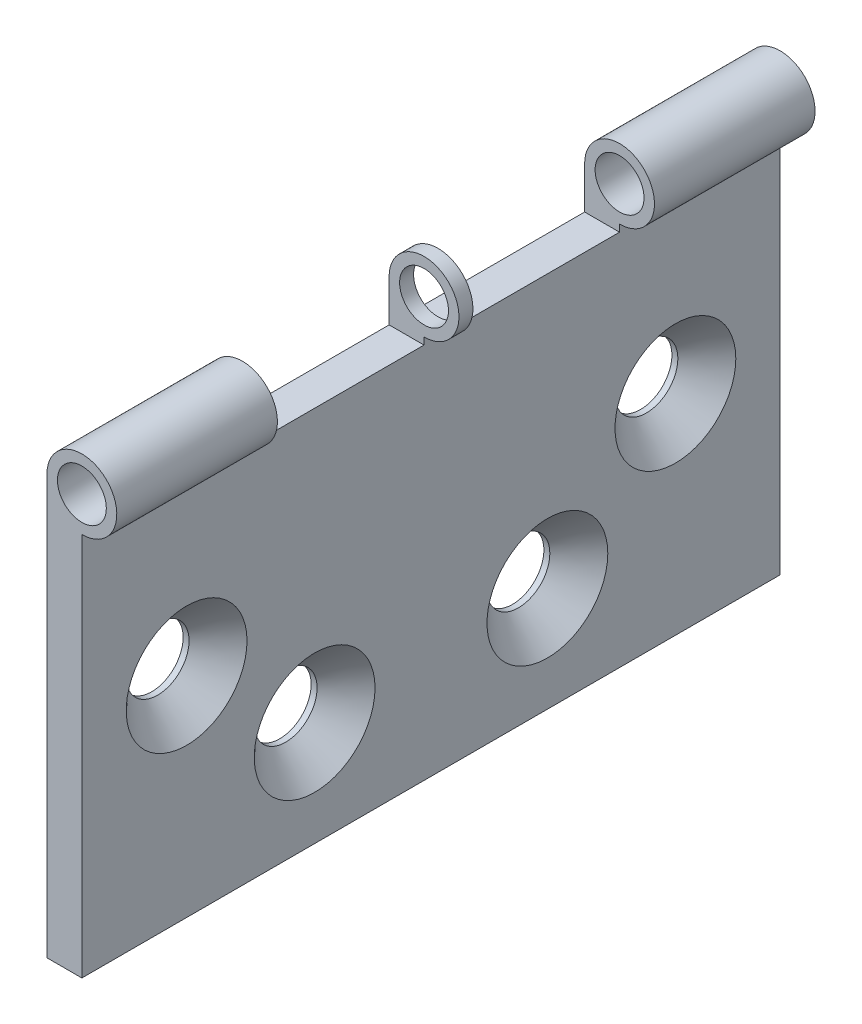
SolidWorks part; units mm, degrees
ref_plane "Front Plane" through (0, 0, 0) normal (0, 0, 1) x (1, 0, 0)
ref_plane "Top Plane" through (0, 0, 0) normal (0, 1, 0) x (1, 0, 0)
ref_plane "Right Plane" through (0, 0, 0) normal (1, 0, 0) x (0, 0, -1)
sketch "Sketch1" plane through (0, 0, 0) normal (0, 0, 1) x (1, 0, 0)
  line L0 (0, 0) -> (0, 60)
  dimension "D1" = 60
extrude "Extrude-Thin1" add sketch "Sketch1" along normal mid plane 100 thin
sketch "Sketch2" plane through (0, 0, 50) normal (0, 0, 1) x (1, 0, 0)
  circle A0 centre (5, 60) radius 5
sweep "Sweep1" add profiles "Sketch2" path edge at (0, 60, 0)
sketch "Sketch3" plane through (0, 0, 50) normal (0, 0, 1) x (1, 0, 0)
  circle A0 centre (5, 60) radius 3.5
  arc A1 (5, 55) -> (0, 60) centre (5, 60) ccw construction
  dimension "D1" = 7
extrude "Cut-Extrude1" cut sketch "Sketch3" against normal through all
hole_wizard "CSK for M8 Flat Head Machine Screw1" positions "Sketch4" profile "Sketch5" countersink size "M8" standard "ANSI Metric" end condition through all
sketch "Sketch4" plane through (5, 0, 0) normal (1, 0, 0) x (0, 0, -1)
  line L0 (-50, 0) -> (-50, 55) construction
  line L1 (-50, 0) -> (50, 0) construction
  point P0 (-35, 30)
  point P2 (-16.6667, 15)
  dimension "D2" = 15
  dimension "D3" = 30
  dimension "D4" = 15
  dimension "D1" = 33.3333
sketch "Sketch5" plane through (5, 30, 35) normal (0, 1, 0) x (0, 0, -1)
  line L0 (0, 0) -> (0, 5)
  line L1 (0, 5) -> (4.5, 5)
  line L2 (4.5, 5) -> (4.5, 4.15)
  line L3 (4.5, 4.15) -> (8.65, 0)
  line L5 (8.65, 0) -> (0, 0)
  line L6 (-4.5, 4.15) -> (-8.65, 0) construction
  line L11 (0, -6.35) -> (0, 107.95) construction
  dimension "Thru Hole Dia." = 9
  dimension "Thru Hole Depth" = 5
  dimension "Near C'Sink Dia." = 17.3
  dimension "Near C'Sink Angle" = 90
mirror "Mirror1" about plane through (0, 0, 0) normal (0, 0, 1) of "CSK for M8 Flat Head Machine Screw1"
sketch "layout for cuts" plane through (5, 0, 0) normal (1, 0, 0) x (0, 0, -1)
  line L0 (-50, 65) -> (-50, 55) construction
  line L1 (50, 55) -> (50, 65) construction
  line L2 (-50, 54) -> (50, 54)
  line L3 (-50, 54) -> (50, 54)
  line L4 (-50, 65) -> (-50, 54)
  line L5 (50, 54) -> (50, 65)
  line L6 (-50, 65) -> (50, 65)
  line L7 (-26, 65) -> (-26, 54)
  line L8 (-2, 65) -> (-2, 54)
  line L9 (0, 0) -> (0, 65) construction
  line L10 (2, 65) -> (2, 54)
  line L11 (26, 65) -> (26, 54)
  dimension "D2" = 24
  dimension "D3" = 24
  dimension "D4" = 100
  dimension "D1" = 1
sketch "Sketch8" plane through (5, 0, 0) normal (1, 0, 0) x (0, 0, -1)
  line L0 (-50, 54) -> (50, 54) construction
  line L1 (50, 54) -> (50, 65) construction
  line L2 (-50, 65) -> (50, 65) construction
  line L3 (-50, 65) -> (-50, 54) construction
  line L4 (-27, 54) -> (-1, 54)
  line L5 (50, 54) -> (50, 65)
  line L6 (-27, 65) -> (-1, 65)
  line L7 (-50, 65) -> (-50, 54)
  line L10 (-27, 65) -> (-27, 54)
  line L11 (-27, 65) -> (-27, 54)
  line L13 (27, 65) -> (27, 54)
  line L14 (27, 65) -> (27, 54)
  line L16 (-1, 65) -> (-1, 54)
  line L17 (-1, 65) -> (-1, 54)
  line L18 (1, 54) -> (27, 54)
  line L19 (1, 65) -> (1, 54)
  line L20 (1, 65) -> (1, 54)
  line L21 (1, 65) -> (27, 65)
  line M14 (50, 55) -> (-50, 55)
  dimension "D1" = 1
  dimension "D2" = 1
  dimension "D3" = 1
  dimension "D4" = 1
extrude "2Cuts" cut sketch "Sketch8" against normal through all and the other way through all contours L17 L6 L11 M14 | L21 L20 L14 M14
sketch "Sketch7" plane through (5, 0, 0) normal (1, 0, 0) x (0, 0, -1)
  line L0 (-50, 54) -> (50, 54) construction
  line L1 (50, 54) -> (50, 65) construction
  line L2 (-50, 65) -> (50, 65) construction
  line L3 (-50, 65) -> (-50, 54) construction
  line L4 (-50, 54) -> (-25, 54)
  line L5 (50, 54) -> (50, 65)
  line L6 (-50, 65) -> (-25, 65)
  line L7 (-50, 65) -> (-50, 54)
  line L8 (-3, 54) -> (3, 54)
  line L9 (-3, 65) -> (3, 65)
  line L10 (25, 54) -> (50, 54)
  line L11 (-25, 65) -> (-25, 54)
  line L12 (-25, 65) -> (-25, 54)
  line L13 (25, 65) -> (25, 54)
  line L14 (25, 65) -> (25, 54)
  line L15 (25, 65) -> (50, 65)
  line L16 (-3, 65) -> (-3, 54)
  line L17 (-3, 65) -> (-3, 54)
  line L19 (3, 65) -> (3, 54)
  line L20 (3, 65) -> (3, 54)
  dimension "D1" = 1
  dimension "D2" = 1
  dimension "D3" = 1
  dimension "D4" = 1
extrude "3Cuts" [suppressed] cut sketch "Sketch7" against normal through all and the other way through all
equation "\"D3@Sketch4\"= \"D1@Sketch1\" / 2"
equation "\"D1@Sketch4\"= \"D1@Extrude-Thin1\" / 3"
equation "\"D3@layout for cuts\" = \"D4@layout for cuts\" / 5"
